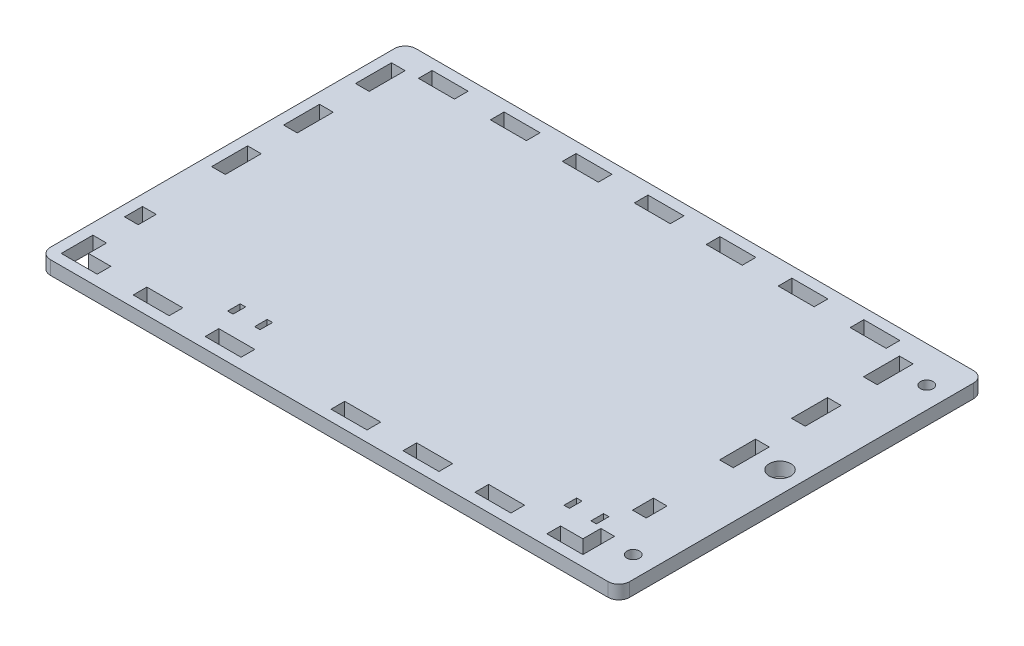
SolidWorks part; units mm, degrees
material "Maple"
ref_plane "Front Plane" through (0, 0, 0) normal (0, 0, 1) x (1, 0, 0)
ref_plane "Top Plane" through (0, 0, 0) normal (0, 1, 0) x (1, 0, 0)
ref_plane "Right Plane" through (0, 0, 0) normal (1, 0, 0) x (0, 0, -1)
sketch "Sketch1" plane through (0, 0, 0) normal (0, 1, 0) x (1, 0, 0)
  line L1 (0, 0) -> (151, 0)
  line L2 (0, 0) -> (0, -101.6)
  line L3 (0, -101.6) -> (151, -101.6)
  line L4 (151, 0) -> (151, -101.6)
  dimension "D1" = 151
  dimension "D2" = 101.6
extrude "Boss-Extrude1" add sketch "Sketch1" along normal blind 3.8
sketch "Sketch3" plane through (0, 0, 0) normal (0, -1, 0) x (1, 0, 0)
  line L0 (0, 87.6) -> (151, 87.6) construction
  line L1 (0, 101.6) -> (151, 101.6) construction
  line L2 (40, 89.35) -> (41.5, 89.35)
  line L3 (40, 89.35) -> (40, 85.85)
  line L4 (40, 85.85) -> (41.5, 85.85)
  line L5 (41.5, 89.35) -> (41.5, 85.85)
  line L6 (40, 89.35) -> (41.5, 85.85) construction
  line L7 (40, 85.85) -> (41.5, 89.35) construction
  line L8 (47.5, 89.35) -> (49, 89.35)
  line L9 (47.5, 89.35) -> (47.5, 85.85)
  line L10 (47.5, 85.85) -> (49, 85.85)
  line L11 (49, 89.35) -> (49, 85.85)
  line L12 (47.5, 89.35) -> (49, 85.85) construction
  line L13 (47.5, 85.85) -> (49, 89.35) construction
  line L14 (133.5, 89.35) -> (135, 89.35)
  line L15 (133.5, 89.35) -> (133.5, 85.85)
  line L16 (133.5, 85.85) -> (135, 85.85)
  line L17 (135, 89.35) -> (135, 85.85)
  line L18 (133.5, 89.35) -> (135, 85.85) construction
  line L19 (133.5, 85.85) -> (135, 89.35) construction
  line L20 (141, 89.35) -> (142.5, 89.35)
  line L21 (141, 89.35) -> (141, 85.85)
  line L22 (141, 85.85) -> (142.5, 85.85)
  line L23 (142.5, 89.35) -> (142.5, 85.85)
  line L24 (141, 89.35) -> (142.5, 85.85) construction
  line L25 (141, 85.85) -> (142.5, 89.35) construction
  line L26 (151, 101.6) -> (151, 0) construction
  line L27 (0, 0) -> (0, 101.6) construction
  point P2 (40.75, 87.6)
  point P7 (48.25, 87.6)
  point P12 (134.25, 87.6)
  point P17 (141.75, 87.6)
  dimension "D1" = 14
  dimension "D2" = 3.5
  dimension "D3" = 1.5
  dimension "D4" = 6
  dimension "D5" = 6
  dimension "D6" = 8.5
  dimension "D7" = 40
extrude "Cut-Extrude1" cut sketch "Sketch3" against normal through all
sketch "Sketch4" plane through (0, 0, 0) normal (0, -1, 0) x (1, 0, 0)
  line L0 (151, 101.6) -> (151, 0) construction
  line L1 (151, 101.6) -> (161, 101.6)
  line L2 (151, 101.6) -> (151, 0)
  line L3 (151, 0) -> (161, 0)
  line L4 (161, 101.6) -> (161, 0)
  line L5 (151, 0) -> (0, 0) construction
  line L6 (0, 101.6) -> (151, 101.6) construction
  dimension "D1" = 10
extrude "Boss-Extrude2" add sketch "Sketch4" against normal through all
sketch "Sketch5" plane through (0, 0, 0) normal (0, -1, 0) x (1, 0, 0)
  line L0 (161, 50.8) -> (0, 50.8) construction
  line L1 (161, 0) -> (161, 101.6) construction
  line L2 (0, 0) -> (0, 101.6) construction
  line L3 (155, 101.6) -> (155, 0) construction
  line L4 (0, 101.6) -> (161, 101.6) construction
  line L5 (161, 0) -> (0, 0) construction
  line L6 (161, 0) -> (161, 101.6) construction
  circle A0 centre (155, 50.8) radius 3
  circle A1 centre (155, 91.6) radius 1.75
  circle A2 centre (155, 10) radius 1.75
  point P18 (161, 50.8)
  dimension "D1" = 6
  dimension "D3" = 3.5
  dimension "D2" = 6
  dimension "D4" = 10
  dimension "D5" = 10
  dimension "D6" = 6
extrude "Cut-Extrude2" cut sketch "Sketch5" against normal through all
fillet "Fillet1" radius 3 2 edges at (0, 1.9, 0) (0, 1.9, 101.6)
fillet "Fillet2" radius 3 2 edges at (161, 1.9, 101.6) (161, 1.9, 0)
sketch "Sketch6" plane through (0, 3.8, 0) normal (0, 1, 0) x (1, 0, 0)
  line L0 (80.5, 0) -> (80.5, -101.6) construction
  line L2 (148, -94) -> (148, -89.8)
  line L3 (148, -89.8) -> (144.2, -89.8)
  line L4 (144.2, -94.8) -> (144.2, -89.8)
  line L5 (148, -81) -> (144.2, -81)
  line L6 (148, -81) -> (148, -75.2)
  line L7 (148, -75.2) -> (144.2, -75.2)
  line L8 (144.2, -81) -> (144.2, -75.2)
  line L9 (148, -56.8) -> (144.2, -56.8)
  line L10 (148, -56.8) -> (148, -46.8)
  line L11 (148, -46.8) -> (144.2, -46.8)
  line L12 (144.2, -56.8) -> (144.2, -46.8)
  line L13 (148, -36.8) -> (144.2, -36.8)
  line L14 (148, -36.8) -> (148, -26.8)
  line L15 (148, -26.8) -> (144.2, -26.8)
  line L16 (144.2, -36.8) -> (144.2, -26.8)
  line L17 (148, -16.8) -> (144.2, -16.8)
  line L18 (148, -16.8) -> (148, -6.8)
  line L19 (148, -6.8) -> (144.2, -6.8)
  line L20 (144.2, -16.8) -> (144.2, -6.8)
  line L21 (140.5, -6.8) -> (130.5, -6.8)
  line L22 (140.5, -6.8) -> (140.5, -3)
  line L23 (140.5, -3) -> (130.5, -3)
  line L24 (130.5, -6.8) -> (130.5, -3)
  line L25 (120.5, -6.8) -> (110.5, -6.8)
  line L26 (120.5, -6.8) -> (120.5, -3)
  line L27 (120.5, -3) -> (110.5, -3)
  line L28 (110.5, -6.8) -> (110.5, -3)
  line L29 (100.5, -6.8) -> (90.5, -6.8)
  line L30 (100.5, -6.8) -> (100.5, -3)
  line L31 (100.5, -3) -> (90.5, -3)
  line L32 (90.5, -6.8) -> (90.5, -3)
  line L33 (80.5, -6.8) -> (70.5, -6.8)
  line L34 (80.5, -6.8) -> (80.5, -3)
  line L35 (80.5, -3) -> (70.5, -3)
  line L36 (70.5, -6.8) -> (70.5, -3)
  line L37 (60.5, -6.8) -> (50.5, -6.8)
  line L38 (60.5, -6.8) -> (60.5, -3)
  line L39 (60.5, -3) -> (50.5, -3)
  line L40 (50.5, -6.8) -> (50.5, -3)
  line L41 (40.5, -6.8) -> (30.5, -6.8)
  line L42 (40.5, -6.8) -> (40.5, -3)
  line L43 (40.5, -3) -> (30.5, -3)
  line L44 (30.5, -6.8) -> (30.5, -3)
  line L45 (20.5, -6.8) -> (10.5, -6.8)
  line L46 (20.5, -6.8) -> (20.5, -3)
  line L47 (20.5, -3) -> (10.5, -3)
  line L48 (10.5, -6.8) -> (10.5, -3)
  line L49 (6.8, -16.8) -> (3, -16.8)
  line L50 (6.8, -16.8) -> (6.8, -6.8)
  line L51 (6.8, -6.8) -> (3, -6.8)
  line L52 (3, -16.8) -> (3, -6.8)
  line L53 (6.8, -36.8) -> (3, -36.8)
  line L54 (6.8, -36.8) -> (6.8, -26.8)
  line L55 (6.8, -26.8) -> (3, -26.8)
  line L56 (3, -36.8) -> (3, -26.8)
  line L57 (6.8, -56.8) -> (3, -56.8)
  line L58 (6.8, -56.8) -> (6.8, -46.8)
  line L59 (6.8, -46.8) -> (3, -46.8)
  line L60 (3, -56.8) -> (3, -46.8)
  line L61 (6.8, -81) -> (3, -81)
  line L62 (6.8, -81) -> (6.8, -76)
  line L63 (6.8, -76) -> (3, -76)
  line L64 (3, -81) -> (3, -76)
  line L66 (6.8, -94.8) -> (6.8, -89.8)
  line L67 (6.8, -89.8) -> (3, -89.8)
  line L68 (3, -94) -> (3, -89.8)
  line L97 (23, -94.8) -> (33, -94.8)
  line L98 (23, -94.8) -> (23, -98.6)
  line L99 (23, -98.6) -> (33, -98.6)
  line L100 (33, -94.8) -> (33, -98.6)
  line L101 (43, -94.8) -> (53, -94.8)
  line L102 (43, -94.8) -> (43, -98.6)
  line L103 (43, -98.6) -> (53, -98.6)
  line L104 (53, -94.8) -> (53, -98.6)
  line L109 (78, -94.8) -> (88, -94.8)
  line L110 (78, -94.8) -> (78, -98.6)
  line L111 (78, -98.6) -> (88, -98.6)
  line L112 (88, -94.8) -> (88, -98.6)
  line L113 (98, -94.8) -> (108, -94.8)
  line L114 (98, -94.8) -> (98, -98.6)
  line L115 (98, -98.6) -> (108, -98.6)
  line L116 (108, -94.8) -> (108, -98.6)
  line L117 (118, -94.8) -> (128, -94.8)
  line L118 (118, -94.8) -> (118, -98.6)
  line L119 (118, -98.6) -> (128, -98.6)
  line L120 (128, -94.8) -> (128, -98.6)
  line L121 (138, -94.8) -> (144.2, -94.8)
  line L122 (138, -94.8) -> (138, -98.6)
  line L123 (138, -98.6) -> (148, -98.6)
  line L124 (148, -94) -> (148, -98.6)
  line L125 (13, -94.8) -> (6.8, -94.8)
  line L126 (13, -94.8) -> (13, -98.6)
  line L127 (13, -98.6) -> (3, -98.6)
  line L128 (3, -94) -> (3, -98.6)
  line L129 (158, 0) -> (3, 0) construction
  line L130 (3, -101.6) -> (158, -101.6) construction
  line L131 (0, -3) -> (0, -98.6) construction
  line L132 (161, -3) -> (161, -98.6) construction
  line L133 (3, -101.6) -> (158, -101.6) construction
  point P104 (0, 0)
  point P105 (80.5, -101.6)
  dimension "D1" = 3
  dimension "D2" = 10
  dimension "D3" = 3.8
  dimension "D4" = 10
  dimension "D5" = 10
  dimension "D6" = 10
  dimension "D7" = 10
  dimension "D8" = 10
  dimension "D9" = 10
  dimension "D10" = 3
  dimension "D11" = 6.8
  dimension "D12" = 10
  dimension "D13" = 3.8
  dimension "D14" = 10
  dimension "D15" = 10
  dimension "D16" = 10
  dimension "D17" = 10
  dimension "D19" = 5
  dimension "D20" = 8.8
  dimension "D21" = 3
  dimension "D22" = 6.8
  dimension "D23" = 13
  dimension "D24" = 10
  dimension "D25" = 3.8
  dimension "D26" = 10
  dimension "D27" = 10
  dimension "D28" = 10
  dimension "D29" = 10
  dimension "D31" = 8.8
  dimension "D32" = 3.8
  dimension "D33" = 10
  dimension "D34" = 10
  dimension "D35" = 10
  dimension "D36" = 10
  dimension "D37" = 25
  dimension "D38" = 10
  dimension "D39" = 10
  dimension "D40" = 10
  dimension "D41" = 10
  dimension "D42" = 10
  dimension "D43" = 10
  dimension "D44" = 10
  dimension "D45" = 8.8
  dimension "D18" = 5
  dimension "D30" = 5.8
extrude "Cut-Extrude3" cut sketch "Sketch6" against normal through all
equation "\"D5@Sketch5\"=\"D4@Sketch5\""
equation "\"D5@Sketch6\"=\"D4@Sketch6\""
equation "\"D6@Sketch6\"=\"D4@Sketch6\""
equation "\"D7@Sketch6\"=\"D4@Sketch6\""
equation "\"D8@Sketch6\"=\"D4@Sketch6\""
equation "\"D9@Sketch6\"=\"D4@Sketch6\""
